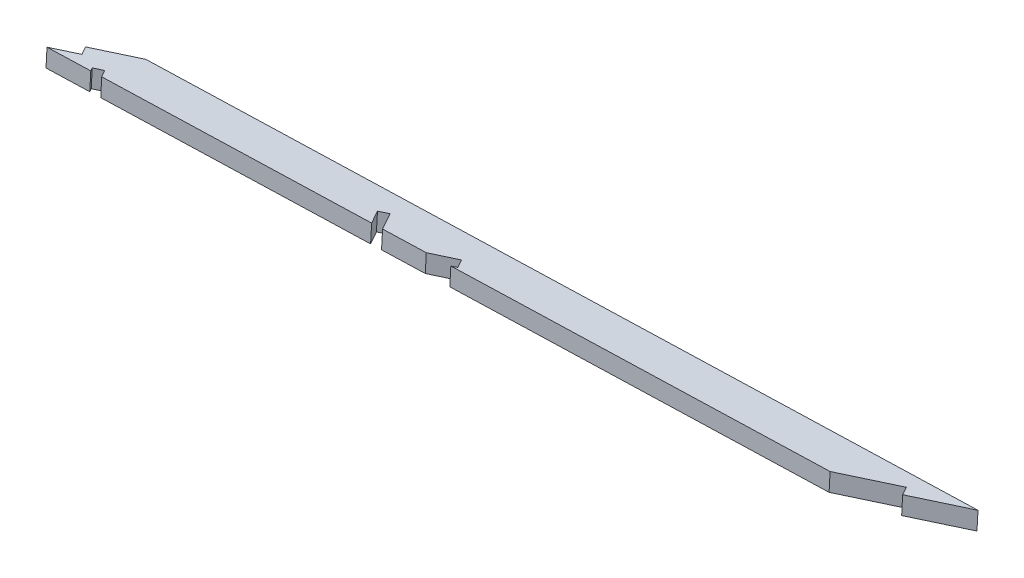
SolidWorks part; units mm, degrees
material "Balsa"
ref_plane "Front Plane" through (0, 0, 0) normal (0, 0, 1) x (1, 0, 0)
ref_plane "Top Plane" through (0, 0, 0) normal (0, 1, 0) x (1, 0, 0)
ref_plane "Right Plane" through (0, 0, 0) normal (1, 0, 0) x (0, 0, -1)
sketch "Sketch2" plane through (1.8581, 36.5912, 26.2272) normal (-0.0507, -0.9987, 0.0043) x (0.9987, -0.0507, 0.0026)
  line L24 (-496.3236, -3.4435) -> (-488.6, -7.7247)
  line L25 (-496.3236, -3.4435) -> (-488.6, -7.7247)
  line L26 (-488.6, -7.7247) -> (-490.1393, -10.5017)
  line L27 (-488.6, -7.7247) -> (-490.1393, -10.5017)
  line L40 (-490.1393, -10.5017) -> (-476.8098, -17.8896)
  line L41 (-476.8098, -17.8896) -> (-213.2206, -40.8279)
  line L42 (-213.2206, -40.8279) -> (-229.8824, -31.5929)
  line L43 (-482.4579, -4.6501) -> (-496.3236, -3.4435)
  line L44 (-490.1393, -10.5017) -> (-476.8098, -17.8896)
  line L45 (-476.8098, -17.8896) -> (-213.2206, -40.8279)
  line L46 (-213.2206, -40.8279) -> (-229.8824, -31.5929)
  line L47 (-482.4579, -4.6501) -> (-496.3236, -3.4435)
  line L54 (-229.8824, -31.5929) -> (-231.4216, -34.3699)
  line L55 (-229.8824, -31.5929) -> (-231.4216, -34.3699)
  line L56 (-231.4216, -34.3699) -> (-248.2736, -25.0295)
  line L57 (-231.4216, -34.3699) -> (-248.2736, -25.0295)
  line L58 (-248.2736, -25.0295) -> (-368.4142, -14.5745)
  line L59 (-248.2736, -25.0295) -> (-368.4142, -14.5745)
  line L60 (-368.4142, -14.5745) -> (-366.8681, -15.4315)
  line L61 (-368.4142, -14.5745) -> (-366.8681, -15.4315)
  line L62 (-366.8681, -15.4315) -> (-368.4074, -18.2084)
  line L63 (-366.8681, -15.4315) -> (-368.4074, -18.2084)
  line L64 (-368.4074, -18.2084) -> (-376.1828, -13.8985)
  line L65 (-368.4074, -18.2084) -> (-376.1828, -13.8985)
  line L130 (-393.4982, -12.3916) -> (-478.9948, -4.9515)
  line L131 (-393.4982, -12.3916) -> (-478.9948, -4.9515)
  line L132 (-478.9948, -4.9515) -> (-480.2967, -7.3002)
  line L133 (-478.9948, -4.9515) -> (-480.2967, -7.3002)
  line L134 (-480.2967, -7.3002) -> (-483.0736, -5.7609)
  line L135 (-480.2967, -7.3002) -> (-483.0736, -5.7609)
  line L136 (-483.0736, -5.7609) -> (-482.4579, -4.6501)
  line L137 (-483.0736, -5.7609) -> (-482.4579, -4.6501)
  line L138 (-376.1828, -13.8985) -> (-390.0351, -12.693)
  line L139 (-376.1828, -13.8985) -> (-390.0351, -12.693)
  line L140 (-390.0351, -12.693) -> (-393.1842, -18.374)
  line L141 (-390.0351, -12.693) -> (-393.1842, -18.374)
  line L142 (-393.1842, -18.374) -> (-395.9611, -16.8347)
  line L143 (-393.1842, -18.374) -> (-395.9611, -16.8347)
  line L144 (-395.9611, -16.8347) -> (-393.4982, -12.3916)
  line L145 (-395.9611, -16.8347) -> (-393.4982, -12.3916)
  dimension "D1" = 0
extrude "Boss-Extrude2" add sketch "Sketch2" along normal blind 6.35
